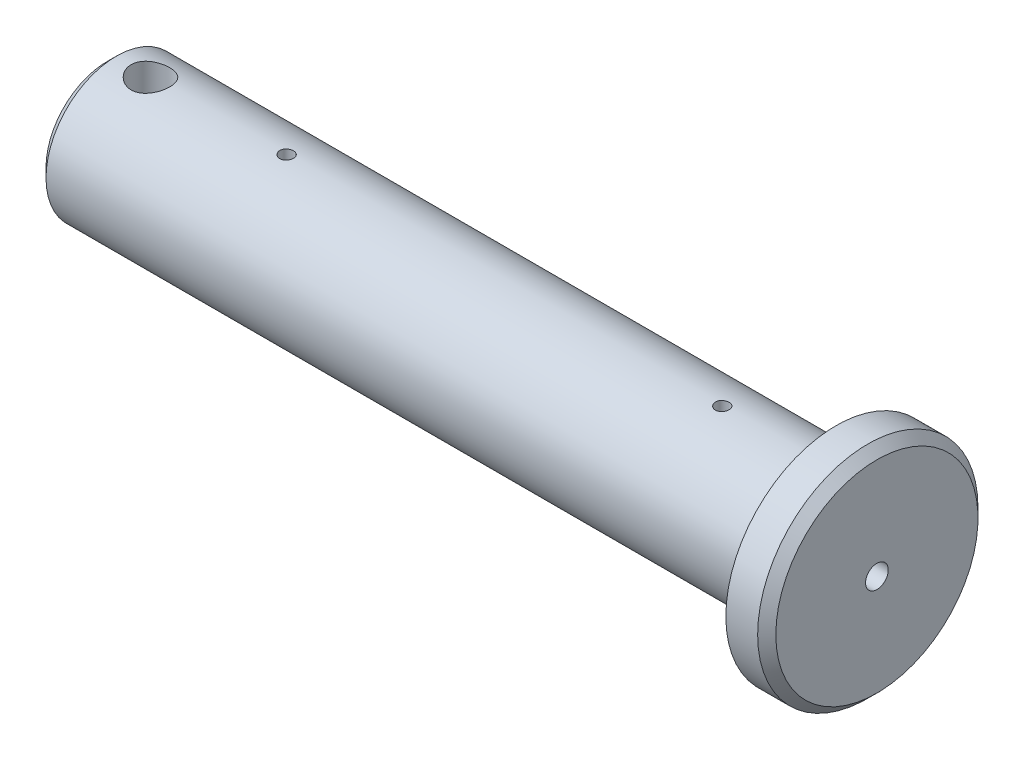
SolidWorks part; units mm, degrees
material "AISI 1045 Aço, trefilado"
ref_plane "Plano frontal" through (0, 0, 0) normal (0, 0, 1) x (1, 0, 0)
ref_plane "Plano superior" through (0, 0, 0) normal (0, 1, 0) x (1, 0, 0)
ref_plane "Plano direito" through (0, 0, 0) normal (1, 0, 0) x (0, 0, -1)
sketch "Esboço1" plane through (0, 0, 0) normal (0, 0, 1) x (1, 0, 0)
  line L0 (-84.69, 0) -> (84.69, 0) construction
  line L1 (84.69, 2.5) -> (84.69, 22.25)
  line L2 (82.69, 24.25) -> (75.69, 24.25)
  line L3 (75.69, 24.25) -> (75.69, 15.5)
  line L4 (75.69, 15.5) -> (-82.69, 15.5)
  line L5 (-84.69, 13.5) -> (-84.69, 0)
  line L6 (-82.69, 15.5) -> (-84.69, 13.5)
  line L7 (84.69, 22.25) -> (82.69, 24.25)
  line L8 (84.69, 2.5) -> (74.69, 2.5)
  line L9 (74.69, 2.5) -> (74.0891, 1.5)
  line L10 (74.0891, 1.5) -> (-50.7887, 1.5)
  line L11 (-50.7887, 1.5) -> (-51.69, 0)
  line L12 (-84.69, 0) -> (-51.69, 0)
  point P4 (84.69, 24.25)
  point P7 (-84.69, 15.5)
  dimension "D1" = 48.5
  dimension "D2" = 31
  dimension "D3" = 169.38
  dimension "D4" = 9
  dimension "D5" = 59
  dimension "D6" = 33
  dimension "D9" = 3
  dimension "D10" = 59
  dimension "D11" = 10
  dimension "D12" = 5
revolve "Revolução1" add sketch "Esboço1" angle 360 about L0
cosmetic thread "Representação de rosca1" parameters "D2"=6
sketch "Esboço2" plane through (0, 0, 0) normal (0, 1, 0) x (1, 0, 0)
  line L0 (84.69, 0) -> (50.66, 0) construction
  line L1 (84.69, -22.25) -> (84.69, 22.25) construction
  line L2 (50.66, 0) -> (-16.3511, 0) construction
  line L3 (-16.3511, 0) -> (-45.22, 0) construction
  line L4 (-45.22, 0) -> (-75.19, 0) construction
  circle A0 centre (50.66, 0) radius 1.5
  circle A1 centre (-45.22, 0) radius 1.5
  dimension "D2" = 3
  dimension "D3" = 129.91
  dimension "D1" = 34.03
extrude "Corte-extrusão1" cut sketch "Esboço2" along normal through all
sketch "Esboço3" plane through (0, 0, 0) normal (0, 1, 0) x (1, 0, 0)
  line L0 (-84.69, 0) -> (-75.19, 0) construction
  line L1 (-84.69, 13.5) -> (-84.69, -13.5) construction
  circle A0 centre (-75.19, 0) radius 4.25
  dimension "D1" = 8.5
  dimension "D2" = 9.5
extrude "Corte-extrusão2" cut sketch "Esboço3" against normal through all both and the other way through all
